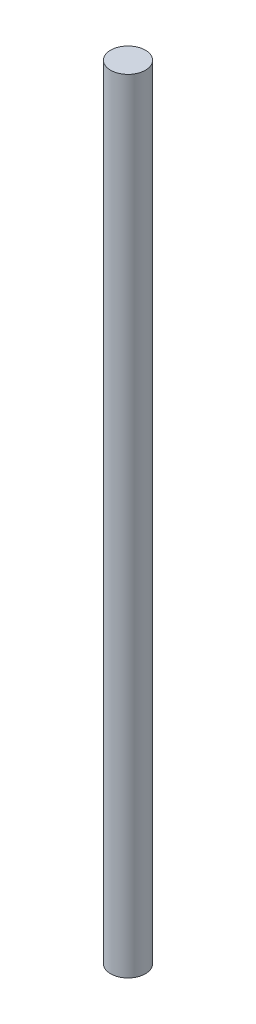
SolidWorks part; units mm, degrees
ref_plane "Front Plane" through (0, 0, 0) normal (0, 0, 1) x (1, 0, 0)
ref_plane "Top Plane" through (0, 0, 0) normal (0, 1, 0) x (1, 0, 0)
ref_plane "Right Plane" through (0, 0, 0) normal (1, 0, 0) x (0, 0, -1)
sketch "Sketch1" plane through (0, 0, 0) normal (0, 1, 0) x (1, 0, 0)
  circle A0 centre (-10.1412, 2.0356) radius 2
  dimension "D1" = 4
extrude "Boss-Extrude1" add sketch "Sketch1" along normal blind 90
